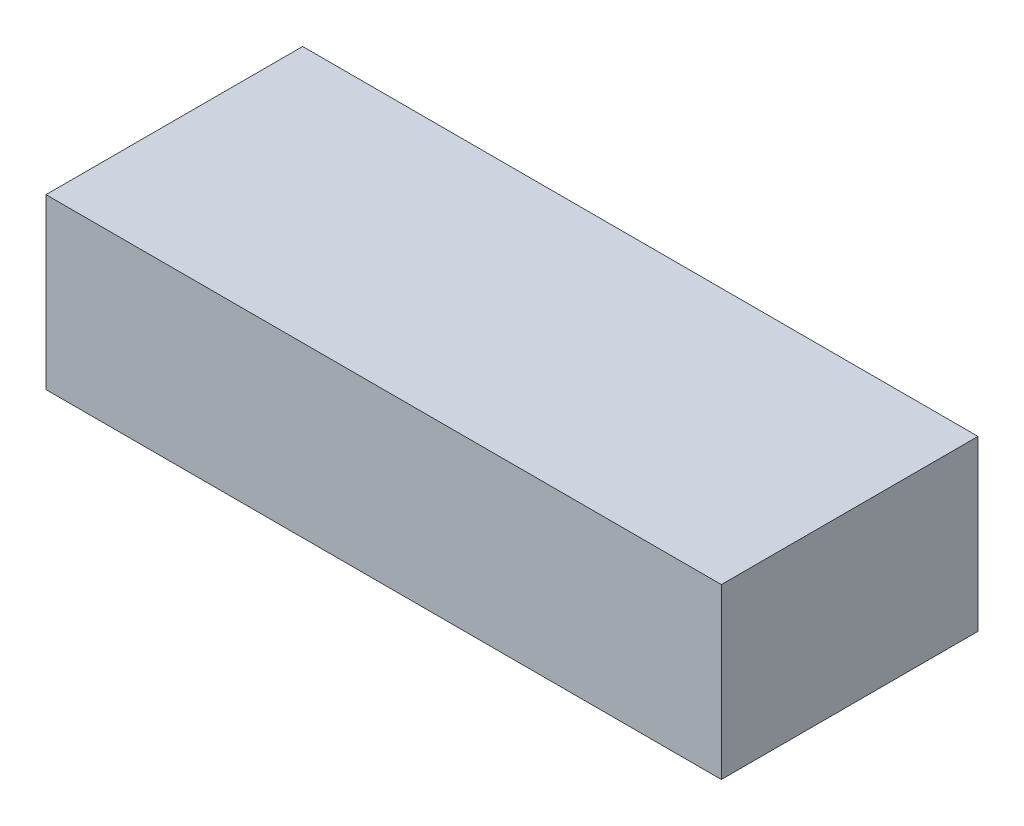
SolidWorks part; units mm, degrees
ref_plane "前视基准面" through (0, 0, 0) normal (0, 0, 1) x (1, 0, 0)
ref_plane "上视基准面" through (0, 0, 0) normal (0, 1, 0) x (1, 0, 0)
ref_plane "右视基准面" through (0, 0, 0) normal (1, 0, 0) x (0, 0, -1)
other "Configuration Table"
sketch "草图1" plane through (0, 0, 0) normal (0, 1, 0) x (1, 0, 0)
  line L1 (0, 0) -> (100, 0)
  line L2 (0, 0) -> (0, -38)
  line L3 (0, -38) -> (100, -38)
  line L4 (100, 0) -> (100, -38)
  dimension "D1" = 38
  dimension "D2" = 100
extrude "凸台-拉伸1" add sketch "草图1" along normal blind 25
